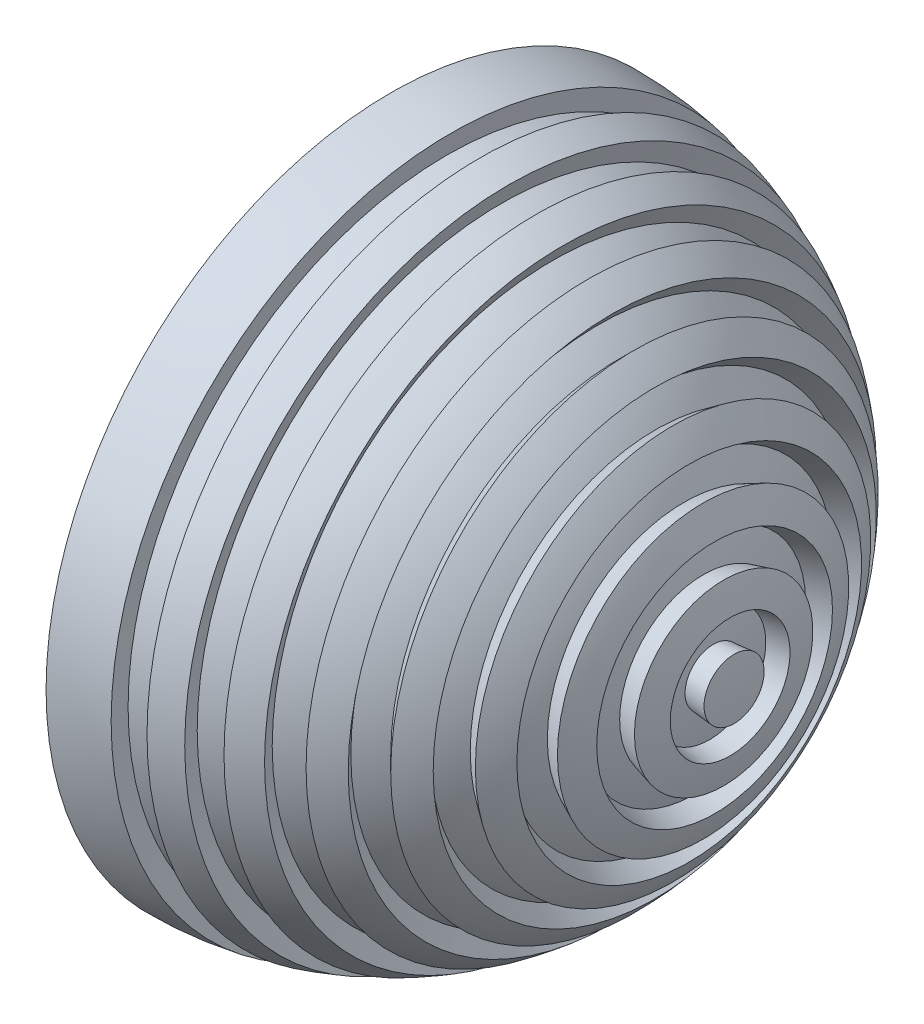
SolidWorks part; units mm, degrees
ref_plane "前视基准面" through (0, 0, 0) normal (0, 0, 1) x (1, 0, 0)
ref_plane "上视基准面" through (0, 0, 0) normal (0, 1, 0) x (1, 0, 0)
ref_plane "右视基准面" through (0, 0, 0) normal (1, 0, 0) x (0, 0, -1)
sketch "草图1" plane through (0, 0, 0) normal (0, 1, 0) x (1, 0, 0)
  line L1 (0, 0) -> (16.5, 0)
  line L2 (0, 0) -> (0, -12)
  line L3 (14.9719, -4.0117) -> (15.9378, -4.2705)
  line L6 (0, -12) -> (0.9318, -15.2313)
  line L7 (0, -15.5) -> (0.9318, -15.2313)
  line L8 (15.441, -1.3509) -> (16.4372, -1.4381)
  line L9 (15.2645, -2.6915) -> (16.2493, -2.8652)
  line L10 (14.5652, -5.3013) -> (15.5049, -5.6433)
  line L11 (14.0478, -6.5506) -> (14.9541, -6.9732)
  line L12 (13.4234, -7.75) -> (14.2894, -8.25)
  line L13 (12.6969, -8.8904) -> (13.516, -9.464)
  line L14 (11.8737, -9.9632) -> (12.6397, -10.606)
  line L15 (10.9602, -10.9602) -> (11.6673, -11.6673)
  line L16 (9.9632, -11.8737) -> (10.606, -12.6397)
  line L17 (8.8904, -12.6969) -> (9.464, -13.516)
  line L18 (7.75, -13.4234) -> (8.25, -14.2894)
  line L19 (6.5506, -14.0478) -> (6.9732, -14.9541)
  line L20 (5.3013, -14.5652) -> (5.6433, -15.5049)
  line L21 (4.0117, -14.9719) -> (4.2705, -15.9378)
  line L22 (2.6915, -15.2645) -> (2.8652, -16.2493)
  line L24 (0, -15.5) -> (0, -16.5)
  line L25 (0, 0) -> (15.441, -1.3509) construction
  line L26 (0, 0) -> (14.9719, -4.0117) construction
  line L27 (1.3509, -15.441) -> (1.4381, -16.4372) [skipped]
  arc A3 (15.2645, -2.6915) -> (15.441, -1.3509) centre (0, 0) ccw
  arc A4 (16.4372, -1.4381) -> (16.5, 0) centre (0, 0) ccw
  arc A5 (14.5652, -5.3013) -> (14.9719, -4.0117) centre (0, 0) ccw
  arc A6 (15.9378, -4.2705) -> (16.2493, -2.8652) centre (0, 0) ccw
  arc A7 (13.4234, -7.75) -> (14.0478, -6.5506) centre (0, 0) ccw
  arc A8 (14.9541, -6.9732) -> (15.5049, -5.6433) centre (0, 0) ccw
  arc A9 (11.8737, -9.9632) -> (12.6969, -8.8904) centre (0, 0) ccw
  arc A10 (13.516, -9.464) -> (14.2894, -8.25) centre (0, 0) ccw
  arc A11 (9.9632, -11.8737) -> (10.9602, -10.9602) centre (0, 0) ccw
  arc A12 (11.6673, -11.6673) -> (12.6397, -10.606) centre (0, 0) ccw
  arc A13 (7.75, -13.4234) -> (8.8904, -12.6969) centre (0, 0) ccw
  arc A14 (9.464, -13.516) -> (10.606, -12.6397) centre (0, 0) ccw
  arc A15 (5.3013, -14.5652) -> (6.5506, -14.0478) centre (0, 0) ccw
  arc A16 (6.9732, -14.9541) -> (8.25, -14.2894) centre (0, 0) ccw
  arc A17 (2.6915, -15.2645) -> (4.0117, -14.9719) centre (0, 0) ccw
  arc A18 (4.2705, -15.9378) -> (5.6433, -15.5049) centre (0, 0) ccw
  arc A19 (0, -16.5) -> (1.4381, -16.4372) centre (0, 0) ccw
  arc A20 (1.4381, -16.4372) -> (2.8652, -16.2493) centre (0, 0) ccw
  arc A21 (0, -15.5) -> (1.3509, -15.441) centre (0, 0) ccw [skipped]
  dimension "D1" = 9
  dimension "D2" = 10
revolve "旋转2" add sketch "草图1" angle 360 about L1
